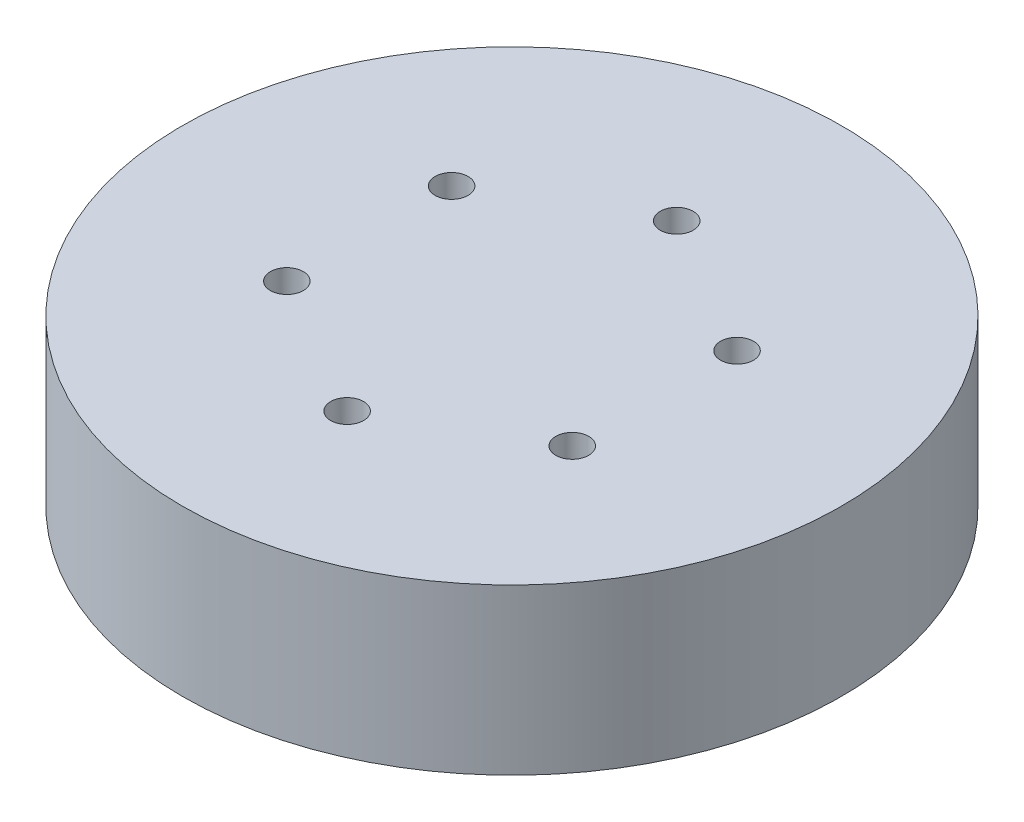
SolidWorks part; units mm, degrees
ref_plane "Front Plane" through (0, 0, 0) normal (0, 0, 1) x (1, 0, 0)
ref_plane "Top Plane" through (0, 0, 0) normal (0, 1, 0) x (1, 0, 0)
ref_plane "Right Plane" through (0, 0, 0) normal (1, 0, 0) x (0, 0, -1)
sketch "Sketch1" plane through (0, 0, 0) normal (0, 1, 0) x (1, 0, 0)
  circle A0 centre (0, 0) radius 25.4
  dimension "D1" = 50.8
extrude "Boss-Extrude1" add sketch "Sketch1" along normal blind 12.7 contours A0
sketch "Sketch2" plane through (0, 12.7, 0) normal (0, 1, 0) x (1, 0, 0)
  circle A0 centre (0, 12.7) radius 1.27
  circle A1 centre (10.9985, 6.35) radius 1.27
  circle A2 centre (10.9985, -6.35) radius 1.27
  circle A3 centre (0, -12.7) radius 1.27
  circle A4 centre (-10.9985, -6.35) radius 1.27
  circle A5 centre (-10.9985, 6.35) radius 1.27
  point P2 (0, 0)
  point P16 (0, 0)
  dimension "D1" = 2.54
  dimension "D2" = 12.7
  dimension "D3" = 6
extrude "Cut-Extrude1" cut sketch "Sketch2" against normal blind 6.35
